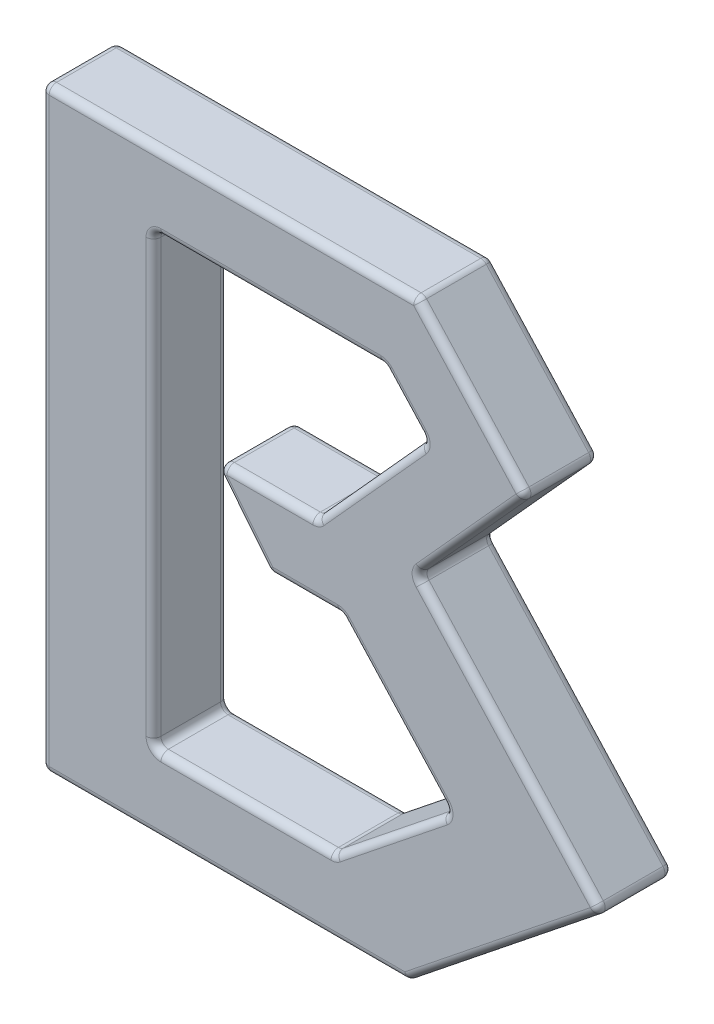
SolidWorks part; units mm, degrees
ref_plane "Front Plane" through (0, 0, 0) normal (0, 0, 1) x (1, 0, 0)
ref_plane "Top Plane" through (0, 0, 0) normal (0, 1, 0) x (1, 0, 0)
ref_plane "Right Plane" through (0, 0, 0) normal (1, 0, 0) x (0, 0, -1)
sketch "Sketch1" plane through (0, 0, 0) normal (0, 0, 1) x (1, 0, 0)
  line L0 (0, 0) -> (0, 80)
  line L1 (0, 80) -> (65, 80) construction
  line L2 (0, 0) -> (65, 0) construction
  line L3 (65, 0) -> (65, 31.801) construction
  line L4 (15, 70) -> (15, 10)
  line L5 (44.9993, 80) -> (50.3564, 80) construction
  line L6 (50.3564, 80) -> (50.3564, 62.7131) construction
  line L7 (0, 80) -> (50.3564, 80)
  line L8 (50.3564, 80) -> (65, 64)
  line L9 (65, 64) -> (50.3564, 47.801)
  line L10 (50.3564, 47.801) -> (75.0827, 20.7844)
  line L11 (75.0827, 20.7844) -> (49.0867, 0)
  line L12 (0, 0) -> (49.0867, 0)
  line L13 (50.3564, 47.801) -> (50.3564, 20.2632) construction
  line L14 (15, 10) -> (39.175, 10)
  line L17 (51.4821, 63.9584) -> (36.8385, 47.7594)
  line L18 (45.9527, 70) -> (51.4821, 63.9584)
  line L19 (15, 70) -> (45.9527, 70)
  line L21 (10, 10) -> (10, 70) construction
  line L22 (10, 70) -> (45.9527, 70) construction
  line L23 (10, 10) -> (45.5805, 10) construction
  line L24 (36.8385, 47.7594) -> (22.7675, 47.7594)
  line L25 (22.7675, 47.7594) -> (30.5407, 38.1607)
  line L26 (30.5407, 38.1607) -> (40.2011, 38.1607)
  line L27 (36.8385, 47.7594) -> (60.4882, 21.9191) construction
  line L29 (54.6505, 22.373) -> (39.175, 10)
  line L30 (40.2011, 38.1607) -> (54.6505, 22.373)
  line L31 (31.4463, 47.7594) -> (31.4313, 47.7428)
  line L35 (14, 14) -> (44.178, 14) construction
  line L36 (14, 66) -> (44.1912, 66) construction
  line L37 (46.0749, 63.9418) -> (31.4313, 47.7428) construction
  line L38 (44.1912, 66) -> (46.0749, 63.9418) construction
  line L39 (31.4313, 47.7428) -> (54.6505, 22.373) construction
  line L40 (54.6505, 22.373) -> (44.178, 14) construction
  line L41 (14, 14) -> (14, 66) construction
  line L42 (60.4882, 21.9191) -> (45.5805, 10) construction
  line L43 (65, 64) -> (65, 80) construction
  dimension "D1" = 10
  dimension "D2" = 14
extrude "Boss-Extrude1" add sketch "Sketch1" against normal blind 10
fillet "Fillet1" radius 1 51 edges at (30.5407, 38.1607, -5) (22.7675, 47.7594, -5) (36.8385, 47.7594, -5) (51.4821, 63.9584, -5) (45.9527, 70, -5) (15, 70, -5) (15, 10, -5) (39.175, 10, -5) (54.6505, 22.373, -5) (40.2011, 38.1607, -5) (0, 80, -5) (50.3564, 80, -5) (65, 64, -5) (50.3564, 47.801, -5) (75.0827, 20.7844, -5) (49.0867, 0, -5) (0, 0, -5) (26.6541, 42.9601, -10) (29.803, 47.7594, -10) (44.1603, 55.8589, -10) (48.7174, 66.9792, -10) (30.4763, 70, -10) (15, 40, -10) (27.0875, 10, -10) (46.9128, 16.1865, -10) (47.4258, 30.2668, -10) (35.3709, 38.1607, -10) (25.1782, 80, -10) (57.6782, 72, -10) (57.6782, 55.9005, -10) (62.7195, 34.2927, -10) (62.0847, 10.3922, -10) (24.5433, 0, -10) (0, 40, -10) (26.6541, 42.9601, 0) (29.803, 47.7594, 0) (44.1603, 55.8589, 0) (48.7174, 66.9792, 0) (30.4763, 70, 0) (15, 40, 0) (27.0875, 10, 0) (46.9128, 16.1865, 0) (47.4258, 30.2668, 0) (35.3709, 38.1607, 0) (25.1782, 80, 0) (57.6782, 72, 0) (57.6782, 55.9005, 0) (62.7195, 34.2927, 0) (62.0847, 10.3922, 0) (24.5433, 0, 0) (0, 40, 0)
